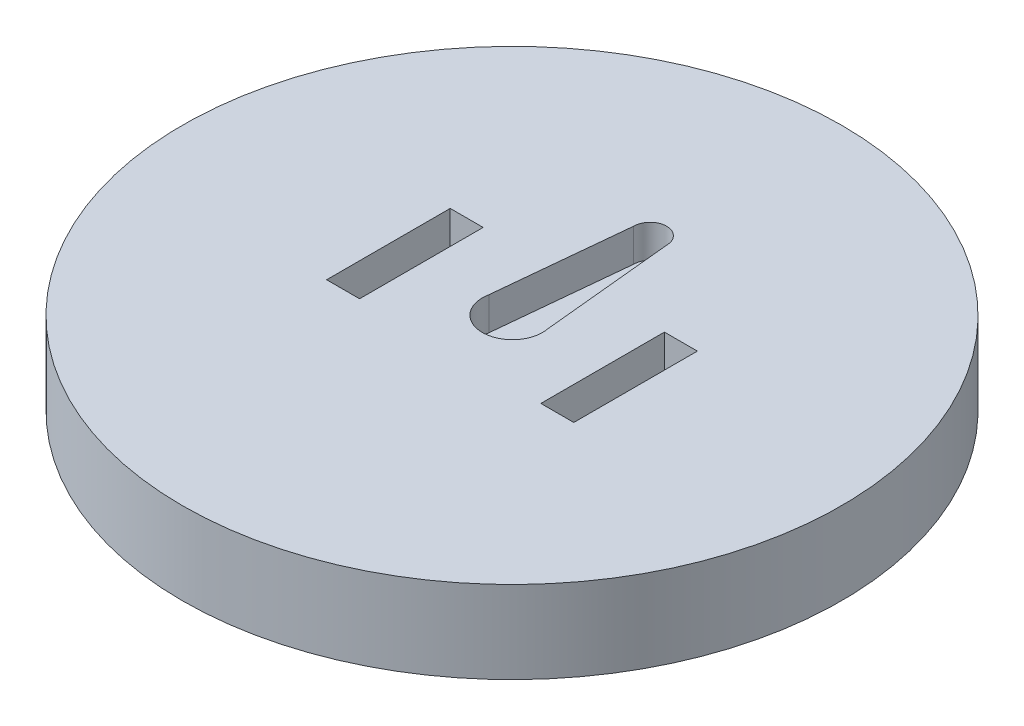
SolidWorks part; units mm, degrees
ref_plane "Front Plane" through (0, 0, 0) normal (0, 0, 1) x (1, 0, 0)
ref_plane "Top Plane" through (0, 0, 0) normal (0, 1, 0) x (1, 0, 0)
ref_plane "Right Plane" through (0, 0, 0) normal (1, 0, 0) x (0, 0, -1)
ref_plane "Bottom Plane" through (0, 0, 0) normal (0, -1, 0) x (1, 0, 0)
sketch "Sketch1" plane through (0, 0, 0) normal (0, 1, 0) x (1, 0, 0)
  circle A0 centre (0, 0) radius 40
  dimension "D1" = 80
extrude "Boss-Extrude1" add sketch "Sketch1" along normal blind 10
sketch "Sketch2" plane through (0, 10, 0) normal (0, 1, 0) x (1, 0, 0)
  line L0 (0, -39.8935) -> (0, 40) construction
  line L1 (-2, 16.7641) -> (2, 16.7641) construction
  line L2 (-2, 16.7641) -> (-3.5801, 0.7641)
  line L4 (2, 16.7641) -> (3.5801, 0.7641)
  arc A0 (-2, 16.7641) -> (2, 16.7641) centre (0, 16.7641) cw
  circle A1 centre (0, 0) radius 40 construction
  arc A2 (-3.5801, 0.7641) -> (3.5801, 0.7641) centre (0, 0.0533) ccw
  point P4 (0, 0.0533)
  point P5 (0, 3.7033)
  point P15 (0, 0.0533)
  dimension "D1" = 3.65
  dimension "D3" = 0.7109
  dimension "D4" = 4
  dimension "D7" = 2
  dimension "D2" = 2
  dimension "D5" = 16
  dimension "D6" = 7.1602
extrude "Cut-Extrude1" cut sketch "Sketch2" against normal blind 4
sketch "Sketch3" plane through (0, 0, 0) normal (0, -1, 0) x (1, 0, 0)
  line L0 (0, -40) -> (0, 40) construction
  line L1 (0, 0) -> (40, 0) construction
  line L2 (15, -7.5) -> (15, 7.5)
  line L3 (-11, -7.5) -> (-15, -7.5)
  line L4 (-11, -7.5) -> (-11, 7.5)
  line L5 (-11, 7.5) -> (-15, 7.5)
  line L6 (-15, -7.5) -> (-15, 7.5)
  line L7 (-11, -7.5) -> (-15, 7.5) construction
  line L8 (-11, 7.5) -> (-15, -7.5) construction
  line L9 (11, -7.5) -> (15, -7.5)
  line L10 (11, -7.5) -> (11, 7.5)
  line L11 (11, 7.5) -> (15, 7.5)
  circle A1 centre (0, 0) radius 40 construction
  point P5 (-13, 0)
  point P7 (0, 0)
  point P15 (0, 0)
  dimension "D1" = 15
  dimension "D2" = 15
  dimension "D3" = 4
  dimension "D4" = 7.5
extrude "Cut-Extrude2" cut sketch "Sketch3" against normal blind 10
